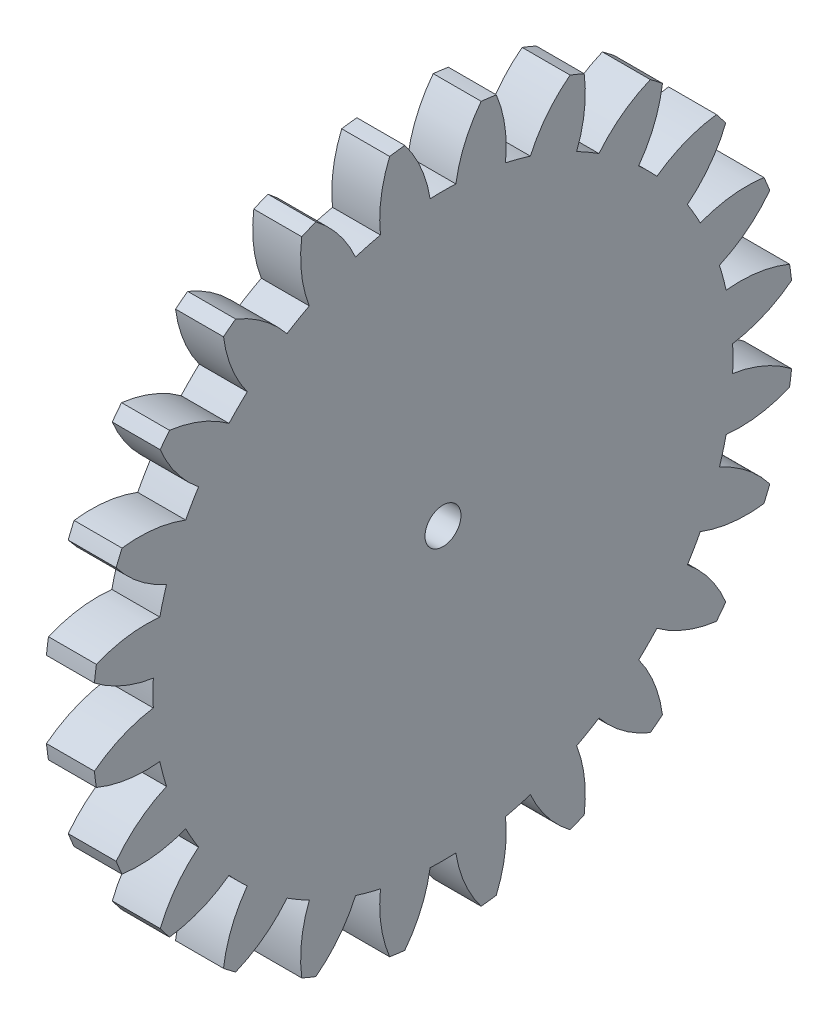
SolidWorks part; units mm, degrees
ref_plane "Plane1" through (0, 0, 0) normal (0, 0, 1) x (1, 0, 0)
ref_plane "Plane2" through (0, 0, 0) normal (0, 1, 0) x (1, 0, 0)
ref_plane "Plane3" through (0, 0, 0) normal (1, 0, 0) x (0, 0, -1)
other "Configuration Table"
sketch "HoldingSke" plane through (0, 0, 0) normal (0, 1, 0) x (1, 0, 0)
  line L0 (0, 0) -> (0.406, -0.1808)
  line L1 (-15, 0) -> (100, 0) construction
  line L2 (0, 0) -> (-2.1039, 2.3779)
  line L3 (0, 0) -> (-11.863, 4.5341)
  line L4 (0, 0) -> (7.8894, 3.5126)
  line L5 (0, 0) -> (-46.8476, -17.4728)
  line L6 (0, 0) -> (-3.3159, -2.2372)
  line L7 (-2.1039, 2.3779) -> (8.6586, 51.2059)
  line L8 (-76.2, 54.61) -> (-75.7, 54.61)
  line L9 (-71.009, 38.7566) -> (-53.1078, 45.2721)
  line L10 (-76.2, 71.12) -> (104.1128, 71.12)
  line L11 (0, 0) -> (-4, 0)
  line L12 (-76.2, 101.6) -> (-76.123, 101.6)
  line L13 (24.9733, 27.94) -> (52.9518, 28.4284)
  line L14 (24.9733, 27.94) -> (24.9743, 27.94)
  line L15 (24.9733, 27.94) -> (100.4006, 29.5858)
  line L16 (-63.627, -2.25) -> (-12.827, -2.25)
  circle A0 centre (0, 0) radius 1.5
  circle A1 centre (0, 0) radius 24.1865
  circle A2 centre (0, 0) radius 37.5
  circle A3 centre (0, 0) radius 1.5
  dimension "MHD" = 48.373
  dimension "Hub_dia" = 75
  dimension "Bore" = 3
  dimension "MBD" = 3
  dimension "Num_teeth" = 24
  dimension "Pitch" = 0.4444
  dimension "Overall_len" = 50
  dimension "Show_teeth" = 24
  dimension "Thickness" = 4
  dimension "OAL" = 50.0001
  dimension "T_dim" = 0.5
  dimension "Ap" = 20
  dimension "H" = 19.05
  dimension "Pitch_radius" = 180.3128
  dimension "Width" = 4
  dimension "Backlash" = 0.077
  dimension "Addendum_fac" = 1
  dimension "Dedendum_fac" = 1.25
  dimension "Clearance_fac" = 0.25
  dimension "Dedendum_add" = 0.001
  dimension "Module" = 2.25
sketch "BasProSke" plane through (0, 0, 0) normal (0, 1, 0) x (1, 0, 0)
  line L0 (-10, 0) -> (60, 0) construction
  line L1 (0, 0) -> (0, 29.25)
  line L2 (0, 0) -> (4, 0)
  line L3 (4, 0) -> (4, 29.25)
  line L4 (4, 29.25) -> (0, 29.25)
  dimension "Thickness" = 4
  dimension "Diameter" = 58.5
revolve "Base-Revolve" add sketch "BasProSke" angle 360 about L0
sketch "TooCutSke" plane through (0, 0, 0) normal (1, 0, 0) x (0, 0, -1)
  line L1 (0, 0) -> (0, 107) construction
  line L2 (0, 0) -> (-1.9006, 26.933) construction
  line L3 (0, 0) -> (-7.0355, 53.4402) construction
  line L4 (-1.9006, 26.933) -> (-3.5178, 26.7201) construction
  arc A0 (1.0746, 24.1626) -> (-1.0746, 24.1626) centre (0, 0) ccw
  arc A1 (3.2031, 29.0996) -> (-3.2031, 29.0996) centre (0, 0) ccw
  circle A2 centre (0, 0) radius 27 construction
  circle A3 centre (0, 0) radius 25.3717 construction
  arc A4 (-1.0746, 24.1626) -> (-3.2031, 29.0996) centre (-11.7443, 22.4899) ccw
  arc A5 (3.2031, 29.0996) -> (1.0746, 24.1626) centre (11.7443, 22.4899) ccw
  dimension "Root_dia" = 48.373
  dimension "Overcut_dia" = 58.5508
  dimension "Pitch_dia" = 54
  dimension "Base_dia" = 50.7434
  dimension "Flank_rad" = 10.8
  dimension "Half_ang" = 7.5
  dimension "Half_CT" = 1.6311
extrude "ToothCut" cut sketch "TooCutSke" along normal through all
fillet "Breaks" [suppressed] radius 0.045
fillet "RootFillets" [suppressed] radius 0.5635
pattern_circular "TeethCuts" count 24 every 15 about axis through (-10, 0, 0) along (1, 0, 0) of "ToothCut", "RootFillets", "Breaks"
sketch "HubNeaOneSke" plane through (0, 0, 0) normal (-1, 0, 0) x (0, 0, 1)
  circle A0 centre (0, 0) radius 24.1865
  dimension "Diameter" = 48.373
extrude "HubNearOne" [suppressed] add sketch "HubNeaOneSke" along normal blind 46.0001
sketch "HubNeaBotSke" plane through (0, 0, 0) normal (-1, 0, 0) x (0, 0, 1)
  circle A0 centre (0, 0) radius 24.1865
  dimension "Diameter" = 48.373
extrude "HubNearBoth" [suppressed] add sketch "HubNeaBotSke" along normal blind 23
ref_plane "FarPln" through (4, 0, 0) normal (1, 0, 0) x (0, 0, -1)
sketch "HubFarSke" plane through (4, 0, 0) normal (1, 0, 0) x (0, 0, -1)
  circle A0 centre (0, 0) radius 24.1865
  dimension "Diameter" = 48.373
extrude "HubFar" [suppressed] add sketch "HubFarSke" along normal blind 23
sketch "BorSke" plane through (0, 0, 0) normal (1, 0, 0) x (0, 0, -1)
  circle A0 centre (0, 0) radius 1.5
  dimension "Diameter" = 3
extrude "Bore" cut sketch "BorSke" along normal mid plane 100.0001
sketch "KeySke" plane through (0, 0, 0) normal (1, 0, 0) x (0, 0, -1)
  line L0 (-0.6, 0) -> (-0.6, 2)
  line L1 (-0.6, 2) -> (0.6, 2)
  line L2 (0.6, 2) -> (0.6, 0)
  line L3 (0, 0) -> (0, 34) construction
  line L4 (-0.6, 0) -> (0.6, 0)
  dimension "Offset" = 2
  dimension "Width" = 1.2
extrude "Keyway" [suppressed] cut sketch "KeySke" along normal mid plane 100.0001
pattern_circular "Keyway2" [suppressed] count 2 every 90 about axis through (-10, 0, 0) along (1, 0, 0)
equation "' \"Module@HoldingSke\" = 6.35"
equation "' \"Num_teeth@HoldingSke\" = 12"
equation "' \"Ap@HoldingSke\" =  20"
equation "' \"Ap@HoldingSke\" = 20"
equation "' \"Width@HoldingSke\" = 0.5 * 25.4"
equation "' \"Hub_dia@HoldingSke\"= 1 * 25.4"
equation "' \"Hub_dia@HoldingSke\" = 1 * 25.4"
equation "' \"Overall_len@HoldingSke\" = 1.0 * 25.4"
equation "' \"Bore@HoldingSke\" = 0.75 * 25.4"
equation "' \"T_dim@HoldingSke\" = 0.1 * 25.4"
equation "' \"Width@KeySke\" = 0.25 * 25.4"
equation "' \"Show_teeth@HoldingSke\" = 13"
equation "' \"Backlash@HoldingSke\" = 0.009 * 25.4"
equation "' \"Addendum_fac@HoldingSke\" = 1.0"
equation "' \"Dedendum_fac@HoldingSke\" = 1.25"
equation "' \"Dedendum_add@HoldingSke\" = 0.00005 * 25.4"
equation "' \"Clearance_fac@HoldingSke\" = 0.25"
equation "\"Pitch@HoldingSke\" = 1 / \"Module@HoldingSke\""
equation "\"Overcut_dia@TooCutSke\" = (\"Num_teeth@HoldingSke\" + 2 * \"Addendum_fac@HoldingSke\") / \"Pitch@HoldingSke\" + 0.002 * 25.4"
equation "\"Pitch_dia@TooCutSke\" = \"Num_teeth@HoldingSke\" / \"Pitch@HoldingSke\""
equation "\"Base_dia@TooCutSke\" = \"Num_teeth@HoldingSke\" / \"Pitch@HoldingSke\" * cos((\"Ap@HoldingSke\"  * 3.14159265 / 180))"
equation "\"Root_dia@TooCutSke\" = (\"Num_teeth@HoldingSke\" + 2) / \"Pitch@HoldingSke\" - 2 * (\"Addendum_fac@HoldingSke\" + \"Dedendum_fac@HoldingSke\") / \"Pitch@HoldingSke\" - \"Dedendum_add@HoldingSke\" * 2"
equation "\"Half_ang@TooCutSke\" = 180 / \"Num_teeth@HoldingSke\""
equation "\"Half_CT@TooCutSke\" = \"Num_teeth@HoldingSke\" / \"Pitch@HoldingSke\" * sin((3.14159265 / 2 / \"Num_teeth@HoldingSke\")) / 2 - 7 * \"Backlash@HoldingSke\" / 4"
equation "\"Flank_rad@TooCutSke\" = \"Num_teeth@HoldingSke\" / \"Pitch@HoldingSke\" / 5"
equation "\"Radius@RootFillets\" = \"Clearance_fac@HoldingSke\" / \"Pitch@HoldingSke\" + \"Dedendum_add@HoldingSke\""
equation "\"Break_rad@Breaks\" = 0.02 / \"Pitch@HoldingSke\""
equation "\"Thickness@HoldingSke\" = \"Width@HoldingSke\""
equation "\"OAL@HoldingSke\" = \"Thickness@HoldingSke\""
equation "\"MHD@HoldingSke\" = (\"Num_teeth@HoldingSke\" + 2) / \"Pitch@HoldingSke\" - 2 * (\"Addendum_fac@HoldingSke\" + \"Dedendum_fac@HoldingSke\")  / \"Pitch@HoldingSke\" - \"Dedendum_add@HoldingSke\" * 2"
equation "\"MBD@HoldingSke\" = (\"Num_teeth@HoldingSke\" + 2) / \"Pitch@HoldingSke\" - 2 * (\"Addendum_fac@HoldingSke\" + \"Dedendum_fac@HoldingSke\")  / \"Pitch@HoldingSke\" - \"Dedendum_add@HoldingSke\" * 2 - 0.002 * 25.4"
equation "\"MHD@HoldingSke\" = ((sgn( \"MHD@HoldingSke\" - \"Hub_dia@HoldingSke\" )-1)*( \"MHD@HoldingSke\" - \"Hub_dia@HoldingSke\" ))/-2+ \"Hub_dia@HoldingSke\""
equation "\"MBD@HoldingSke\" = ((sgn( \"MBD@HoldingSke\" - \"Bore@HoldingSke\" )-1)*( \"MBD@HoldingSke\" - \"Bore@HoldingSke\" ))/-2+ \"Bore@HoldingSke\""
equation "\"OAL@HoldingSke\" = ((sgn( \"OAL@HoldingSke\" - \"Overall_len@HoldingSke\" )+1)*( \"OAL@HoldingSke\" - \"Overall_len@HoldingSke\" ))/2 + \"Overall_len@HoldingSke\" + 0.000002 * 25.4"
equation "\"Num_teeth@TeethCuts\" = int( \"Show_teeth@HoldingSke\" ) + 1"
equation "\"Num_teeth@TeethCuts\" = ((sgn( \"Num_teeth@TeethCuts\" - \"Num_teeth@HoldingSke\" )-1)*( \"Num_teeth@TeethCuts\" - \"Num_teeth@HoldingSke\" ))/-2+ \"Num_teeth@HoldingSke\""
equation "\"Num_teeth@TeethCuts\" = ((sgn( \"Num_teeth@TeethCuts\" - 2.0)+1)*( \"Num_teeth@TeethCuts\" - 2.0))/2 +2.0"
equation "\"Angle@TeethCuts\" = 360.0 / \"Num_teeth@HoldingSke\""
equation "\"Diameter@BasProSke\" = (\"Num_teeth@HoldingSke\" + 2 * \"Addendum_fac@HoldingSke\") / \"Pitch@HoldingSke\""
equation "\"Thickness@BasProSke\"  = \"Thickness@HoldingSke\""
equation "' \"Fillet_rad@BasProSke\" =  \"Thickness@HoldingSke\" * 0.05"
equation "' \"Fillet_rad@BasProSke\" = \"Thickness@HoldingSke\" * 0.05"
equation "\"MHD@HoldingSke\" = ((sgn( \"MHD@HoldingSke\" - \"Root_dia@TooCutSke\" )-1)*( \"MHD@HoldingSke\" - \"Root_dia@TooCutSke\" ))/-2+ \"Root_dia@TooCutSke\""
equation "\"Diameter@HubNeaOneSke\" = \"MHD@HoldingSke\""
equation "\"Length@HubNearOne\" = \"OAL@HoldingSke\" - \"Thickness@BasProSke\""
equation "\"Diameter@HubNeaBotSke\" = \"MHD@HoldingSke\""
equation "\"Length@HubNearBoth\" = ( \"OAL@HoldingSke\" - \"Thickness@BasProSke\" ) / 2.0"
equation "\"Thickness@FarPln\" = \"Thickness@BasProSke\""
equation "\"Diameter@HubFarSke\" = \"MHD@HoldingSke\""
equation "\"Length@HubFar\" = ( \"OAL@HoldingSke\" - \"Thickness@BasProSke\" ) / 2.0"
equation "\"Diameter@BorSke\" = \"MBD@HoldingSke\""
equation "\"D1@Bore\" = \"OAL@HoldingSke\" * 2.0"
equation "\"D1@Keyway\" = \"OAL@HoldingSke\" * 2.0"
equation "\"Offset@KeySke\" = \"T_dim@HoldingSke\" + \"MBD@HoldingSke\" / 2.0"
